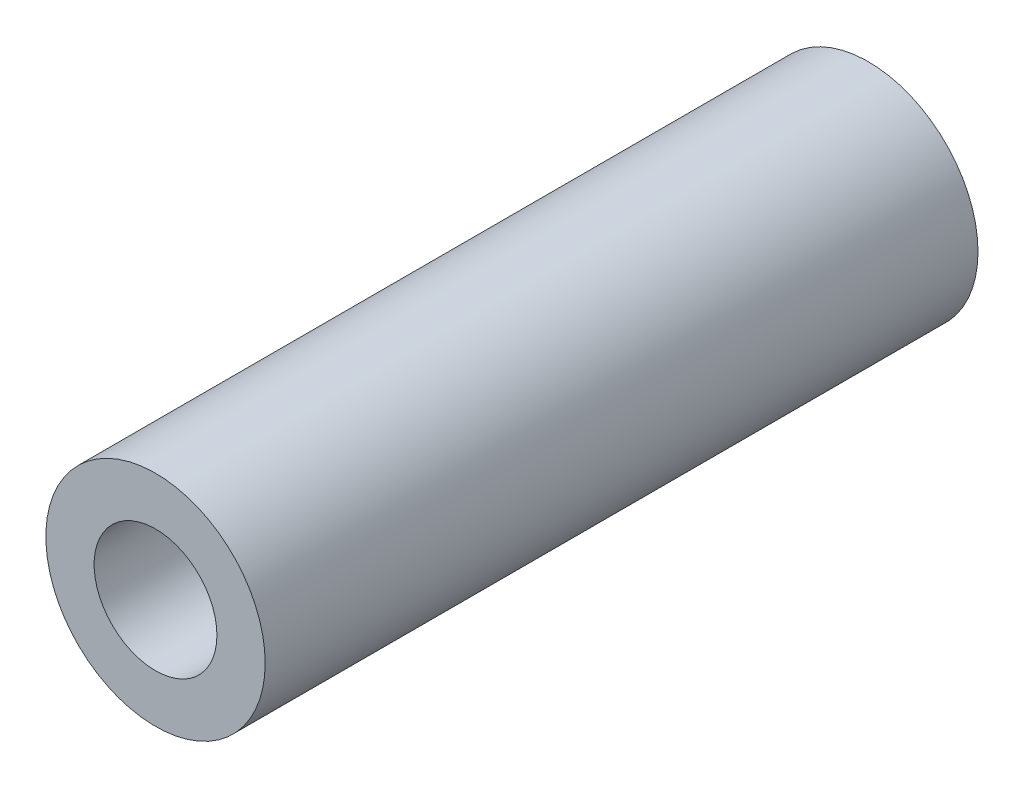
SolidWorks part; units mm, degrees
ref_plane "Front Plane" through (0, 0, 0) normal (0, 0, 1) x (1, 0, 0)
ref_plane "Top Plane" through (0, 0, 0) normal (0, 1, 0) x (1, 0, 0)
ref_plane "Right Plane" through (0, 0, 0) normal (1, 0, 0) x (0, 0, -1)
sketch "Sketch1" plane through (0, 0, 0) normal (0, 0, 1) x (1, 0, 0)
  circle A0 centre (0, 0) radius 3.175
  circle A1 centre (0, 0) radius 1.778
  dimension "OD" = 6.35
  dimension "ID" = 3.556
extrude "Extrude1" add sketch "Sketch1" along normal mid plane 20.6375
sketch "Sketch2" plane through (0, 0, 0) normal (1, 0, 0) x (0, 0, -1)
  line L0 (-10.3187, -1.778) -> (10.3187, -1.778) construction
  line L3 (10.3187, 1.778) -> (-10.3187, 1.778) construction
  line L5 (-10.3187, -1.778) -> (10.3187, -1.778)
  line L6 (10.3187, 1.778) -> (-10.3187, 1.778)
sketch "Sketch4" plane through (0, 0, 10.3187) normal (0, 0, 1) x (1, 0, 0)
  line L0 (0, 0) -> (-1.2572, 1.2572)
  line L1 (0, -2.1828) -> (0, 2.1828) construction
  circle A0 centre (0, 0) radius 1.778 construction
  dimension "D1" = 45
